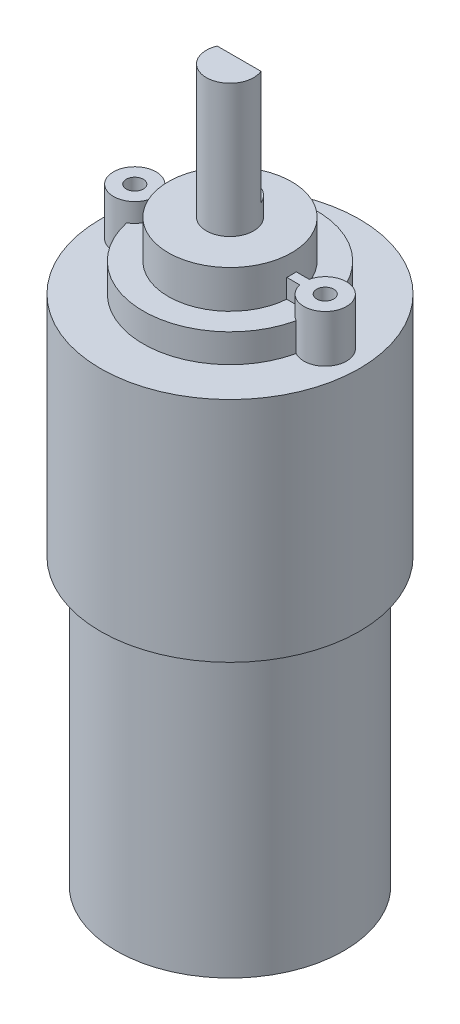
SolidWorks part; units mm, degrees
ref_plane "Alzado" through (0, 0, 0) normal (0, 0, 1) x (1, 0, 0)
ref_plane "Planta" through (0, 0, 0) normal (0, 1, 0) x (1, 0, 0)
ref_plane "Vista lateral" through (0, 0, 0) normal (1, 0, 0) x (0, 0, -1)
sketch "Croquis1" plane through (0, 0, 0) normal (0, 0, 1) x (1, 0, 0)
  line L0 (0, 65.6872) -> (0, -89.1873) construction
  line L1 (0, 30.5) -> (-6.5, 30.5)
  line L2 (-6.5, 30.5) -> (-6.5, 26.5)
  line L3 (-6.5, 26.5) -> (-9.15, 26.5)
  line L4 (-9.15, 26.5) -> (-9.15, 23.5)
  line L5 (-9.15, 23.5) -> (-13.65, 23.5)
  line L6 (-13.65, 23.5) -> (-13.65, -0.5)
  line L7 (-13.65, -0.5) -> (-12, -0.5)
  line L8 (-12, -0.5) -> (-12, -30.5)
  line L9 (-12, -30.5) -> (0, -30.5)
  line L10 (0, -30.5) -> (0, 30.5)
  line L11 (0, 30.5) -> (0, 44.5)
  line L12 (0, 44.5) -> (-2.5, 44.5)
  line L13 (-2.5, 44.5) -> (-2.5, 30.5)
  line L14 (-2.5, 30.5) -> (0, 30.5)
  point P5 (0, 0)
  dimension "D1" = 6.5
  dimension "D2" = 4
  dimension "D3" = 9.15
  dimension "D4" = 13.65
  dimension "D5" = 24
  dimension "D6" = 30
  dimension "D7" = 3
  dimension "D8" = 12
  dimension "D9" = 14
  dimension "D10" = 2.5
revolve "Revolución1" add sketch "Croquis1" angle 360 about L0
sketch "Croquis2" plane through (0, 44.5, 0) normal (0, 1, 0) x (1, 0, 0)
  line L0 (-2.3083, 0.96) -> (2.3083, 0.96)
  circle A1 centre (0, 0) radius 2.5
  circle A2 centre (0, 0) radius 2.5
  circle M3 centre (0, 0) radius 2.5
  dimension "D2" = 0.96
  dimension "D1" = 0
extrude "Cortar-Extruir1" cut sketch "Croquis2" against normal blind 12 contours L0 M3
sketch "Croquis4" plane through (0, 23.5, 0) normal (0, 1, 0) x (1, 0, 0)
  line L0 (0, 5.4331) -> (0, -4.2682) construction
  line L1 (9, 0.5) -> (-9, 0.5)
  line L2 (0, 0.5) -> (0, -0.5)
  line L3 (9, -0.5) -> (-9, -0.5)
  line L4 (-9, 0.5) -> (-9, -0.5)
  line L5 (-12.29, 7.8034) -> (-12.29, -7.8344) construction
  line L6 (0, 0) -> (-16.243, 0) construction
  line L7 (9, 0.5) -> (9, -0.5)
  circle A0 centre (-10.04, 0) radius 2.25
  circle A1 centre (-10.04, 0) radius 0.9
  circle A2 centre (10.04, 0) radius 0.9
  circle A3 centre (10.04, 0) radius 2.25
  point P10 (0, 0)
  circle M11 centre (0, 0) radius 9.15
  dimension "D1" = 1.8
  dimension "D2" = 4.5
  dimension "D3" = 1
  dimension "D4" = 12.29
  dimension "D5" = 9
extrude "Saliente-Extruir1" add sketch "Croquis4" along normal blind 5 contours A1 A0 M11 | A1 A0 L3 L4 L1 M11 | A0 L3 L2 L1 | L3 A3 L1 L2 | A3 A2 L1 L7 L3 M11 | A3 L3 L7 L1 | A3 A2 M11 | L3 A0 L1 L4
